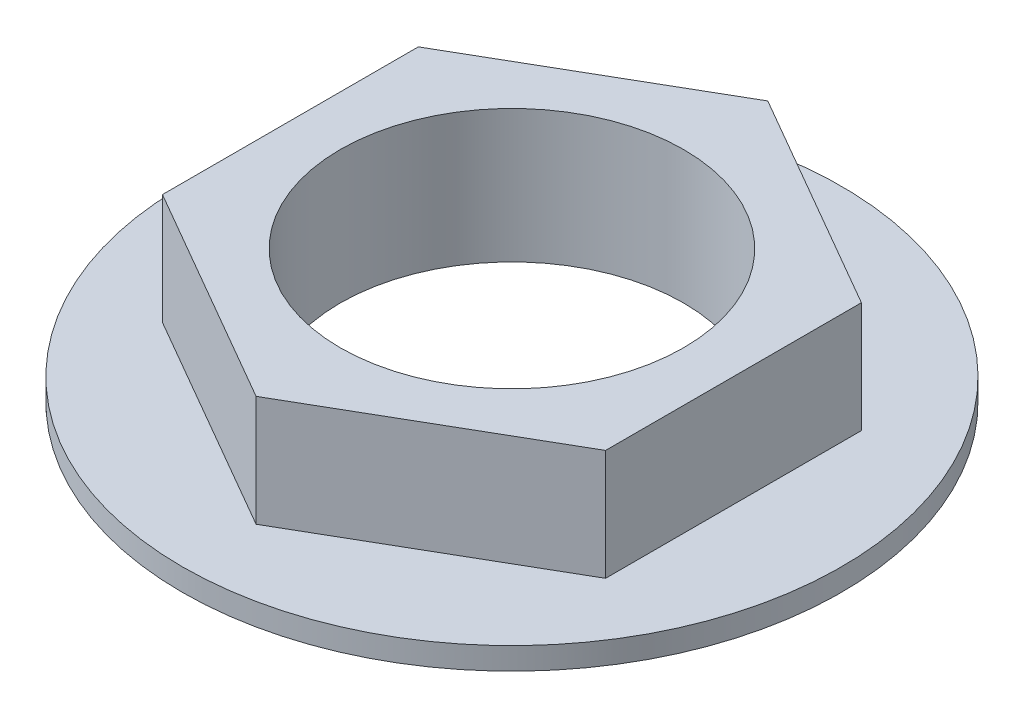
SolidWorks part; units mm, degrees
ref_plane "Vorne" through (0, 0, 0) normal (0, 0, 1) x (1, 0, 0)
ref_plane "Oben" through (0, 0, 0) normal (0, 1, 0) x (1, 0, 0)
ref_plane "Rechts" through (0, 0, 0) normal (1, 0, 0) x (0, 0, -1)
sketch "Sketch1" plane through (0, 0, 0) normal (0, 1, 0) x (1, 0, 0)
  circle A0 centre (0, 0) radius 5.95
  circle A1 centre (0, 0) radius 3.1
  dimension "D1" = 11.9
  dimension "D2" = 6.2
extrude "Boss-Extrude1" add sketch "Sketch1" against normal blind 0.4
sketch "Sketch2" plane through (0, 0, 0) normal (0, 1, 0) x (1, 0, 0)
  line L1 (-4, -2.3094) -> (0, -4.6188)
  line L2 (0, -4.6188) -> (4, -2.3094)
  line L3 (4, -2.3094) -> (4, 2.3094)
  line L4 (4, 2.3094) -> (0, 4.6188)
  line L5 (0, 4.6188) -> (-4, 2.3094)
  line L6 (-4, 2.3094) -> (-4, -2.3094)
  circle A0 centre (0, 0) radius 3.1
  circle A1 centre (0, 0) radius 4 construction
  dimension "D1" = 6.2
  dimension "D2" = 8
extrude "Boss-Extrude2" add sketch "Sketch2" along normal blind 2
